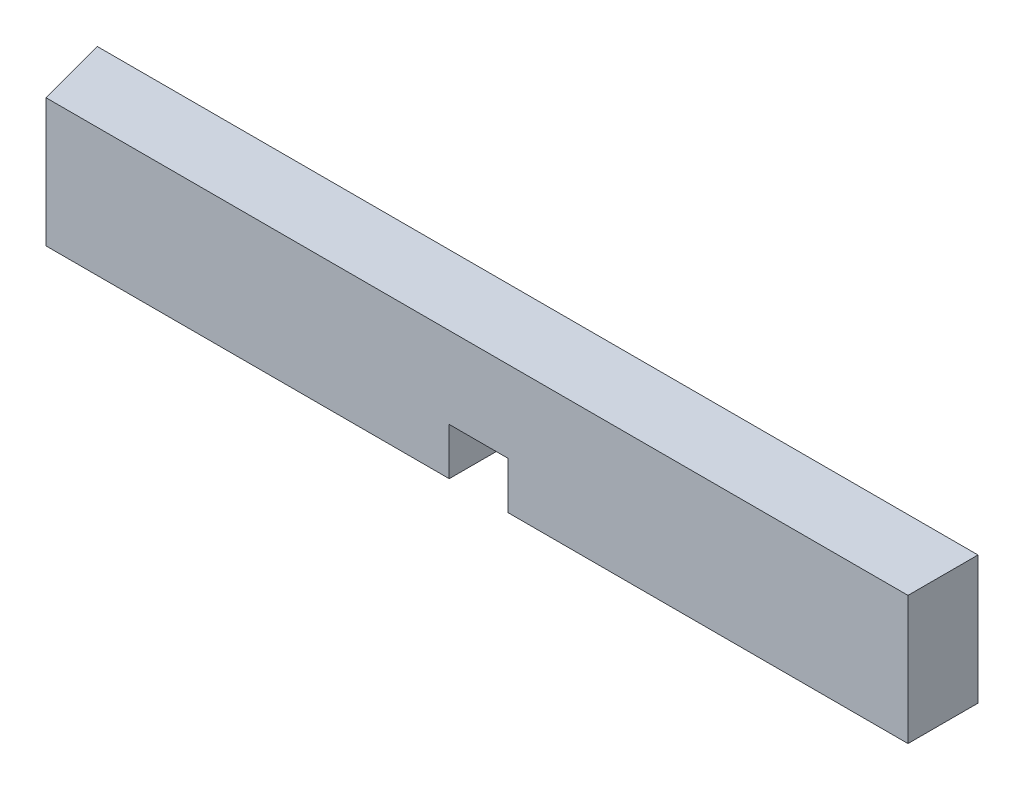
SolidWorks part; units mm, degrees
material "AISI 1020"
ref_plane "Alzado" through (0, 0, 0) normal (0, 0, 1) x (1, 0, 0)
ref_plane "Planta" through (0, 0, 0) normal (0, 1, 0) x (1, 0, 0)
ref_plane "Vista lateral" through (0, 0, 0) normal (1, 0, 0) x (0, 0, -1)
sketch "Croquis1" plane through (0, 0, 0) normal (0, 0, 1) x (1, 0, 0)
  line L1 (0, 0) -> (58.7375, 0)
  line L2 (0, 0) -> (0, 8.6614)
  line L3 (0, 8.6614) -> (58.7375, 8.6614)
  line L4 (58.7375, 0) -> (58.7375, 8.6614)
  dimension "D1" = 58.7375
  dimension "D2" = 8.6614
extrude "Saliente-Extruir1" add sketch "Croquis1" along normal blind 4.7244
sketch "Croquis2" plane through (0, 0, 0) normal (0, 0, 1) x (1, 0, 0)
  line L0 (0, 0) -> (58.7375, 0) construction
  line L1 (27.7812, 0) -> (31.75, 0)
  line L2 (27.7812, 0) -> (27.7812, 3.175)
  line L3 (27.7812, 3.175) -> (31.75, 3.175)
  line L4 (31.75, 0) -> (31.75, 3.175)
  line L5 (0, 8.6614) -> (0, 0) construction
  dimension "D1" = 3.9688
  dimension "D2" = 3.175
  dimension "D3" = 27.7812
extrude "Cortar-Extruir2" cut sketch "Croquis2" against normal through all and the other way through all
sketch "Croquis4" plane through (0, 8.6614, 0) normal (0, 1, 0) x (1, 0, 0)
  line L0 (58.7375, 0) -> (0.5715, 0) construction
  line L1 (58.7375, 0) -> (0, 0) construction
  line L2 (0, -2.3622) -> (4.2357, -2.3622) construction
  line L5 (0, -2.5012) -> (0, -2.2232)
  line L9 (0, -4.7244) -> (0, 0) construction
  line L12 (0.5715, -4.7244) -> (0, -4.7244)
  line L13 (0, -2.2232) -> (0.5715, -4.7244)
  line L14 (0, -2.2232) -> (0, -4.7244)
  dimension "D1" = 58.166
extrude "Cortar-Extruir4" cut sketch "Croquis4" against normal through all contours L13 L12 L14
sketch "Croquis5" plane through (0, 8.6614, 0) normal (0, 1, 0) x (1, 0, 0)
  line L0 (58.7375, -4.7244) -> (0.5715, -4.7244) construction
  line L4 (58.7375, -2.3622) -> (-18.7941, -2.3622) construction
  line L5 (58.7375, -4.7244) -> (58.7375, 0) construction
  line L6 (-0.6985, 0) -> (0.2857, 0)
  line L7 (0.5715, -4.7244) -> (-0.6985, 0)
  line L8 (0.2857, 0) -> (0.5715, -4.7244)
extrude "Saliente-Extruir2" add sketch "Croquis5" against normal up to vertex (8.6614 mm away) contours L6 L8 L7
